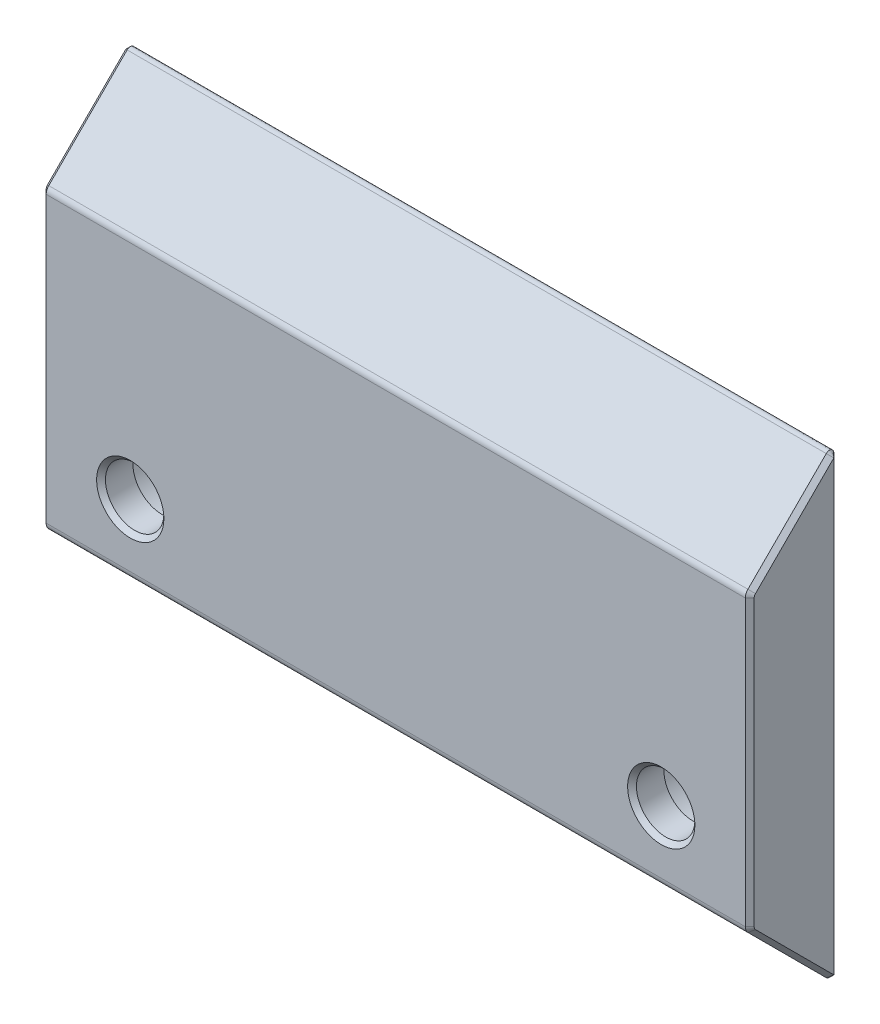
SolidWorks part; units mm, degrees
ref_plane "Top Plane" through (0, 0, 0) normal (0, 0, 1) x (1, 0, 0)
ref_plane "Front Plane" through (0, 0, 0) normal (0, 1, 0) x (1, 0, 0)
ref_plane "Right Plane" through (0, 0, 0) normal (1, 0, 0) x (0, 0, -1)
sketch "Sketch2" plane through (0, 0, 0) normal (1, 0, 0) x (0, 0, -1)
  line L0 (0, 0) -> (0, 53)
  line L1 (0, 53) -> (-10, 43)
  line L2 (-10, 43) -> (-10, 10)
  line L3 (-10, 10) -> (0, 0)
  dimension "D1" = 45
  dimension "D2" = 45
  dimension "D3" = 53
  dimension "D4" = 10
extrude "Boss-Extrude1" add sketch "Sketch2" along normal blind 80
sketch "Sketch4" plane through (0, 0, 0) normal (0, 0, -1) x (-1, 0, 0)
  line L0 (-70, 17.5) -> (-10, 17.5)
  line L1 (-80, 0) -> (-80, 53) construction
  line L2 (-80, 53) -> (0, 53) construction
  dimension "D1" = 60
  dimension "D2" = 10
  dimension "D3" = 35.5
hole_wizard "CBORE for M6 Hex Socket Head Cap Screw1" positions "Sketch7" profile "Sketch8" counterbore size "M6" standard "DIN" end condition through all
sketch "Sketch7" plane through (0, 0, 0) normal (0, 0, -1) x (-1, 0, 0)
  point P0 (-70, 17.5)
  point P3 (-10, 17.5)
sketch "Sketch8" plane through (70, 17.5, 0) normal (1, 0, 0) x (0, 1, 0)
  line L0 (0, 0) -> (0, 10)
  line L1 (0, 10) -> (3.3, 10)
  line L3 (3.3, 10) -> (3.3, 6.4)
  line L4 (3.3, 6.4) -> (5.5, 6.4)
  line L5 (5.5, 6.4) -> (5.5, 0)
  line L7 (5.5, 0) -> (0, 0)
  line L11 (0, -6.35) -> (0, 107.95) construction
  dimension "Thru Hole Dia." = 6.6
  dimension "Thru Hole Depth" = 10
  dimension "C'Bore Dia." = 11
  dimension "C'Bore Depth" = 6.4
fillet "Fillet1" radius 0.5 2 edges at (40, 53, 0) (40, 0, 0)
fillet "Fillet2" radius 1 2 edges at (40, 43, 10) (40, 10, 10)
chamfer "Chamfer1" distance 0.5 angle 45 18 edges at (0, 10.0315, 9.9239) (0, 5.2803, 5.2803) (0, 0.7452, 0.3087) (0, 26.5, 0) (0, 52.2548, 0.3087) (0, 47.7197, 5.2803) (0, 42.9685, 9.9239) (0, 26.5, 10) (80, 52.2548, 0.3087) (80, 26.5, 0) (80, 0.7452, 0.3087) (80, 5.2803, 5.2803) (80, 10.0315, 9.9239) (80, 26.5, 10) (80, 42.9685, 9.9239) (80, 47.7197, 5.2803) (6.7, 17.5, 10) (66.7, 17.5, 10)
chamfer "Chamfer2" distance 0.5 angle 45 2 edges at (64.5, 17.5, 0) (4.5, 17.5, 0)
